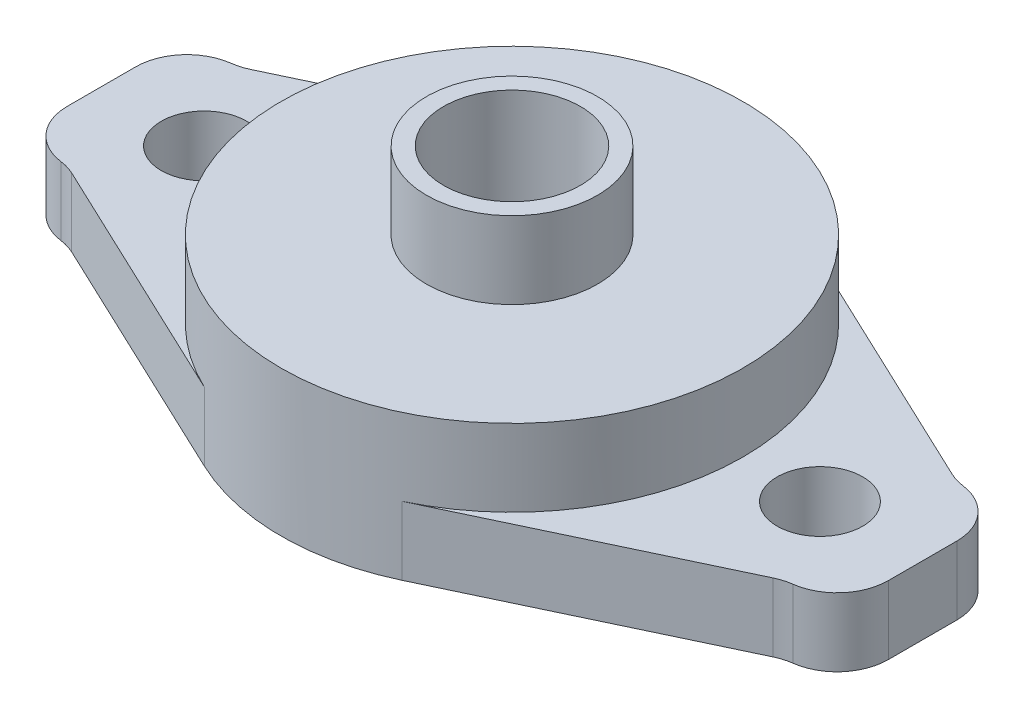
SolidWorks part; units mm, degrees
material "锌 AC41A 合金，作为铸件"
ref_plane "前视基准面" through (0, 0, 0) normal (0, 0, 1) x (1, 0, 0)
ref_plane "上视基准面" through (0, 0, 0) normal (0, 1, 0) x (1, 0, 0)
ref_plane "右视基准面" through (0, 0, 0) normal (1, 0, 0) x (0, 0, -1)
sketch "草图1" plane through (0, 0, 0) normal (0, 1, 0) x (1, 0, 0)
  line L0 (0, 0) -> (18, 0) construction
  line L1 (-20.4991, 5.237) -> (-5.773, 12.2034)
  line L2 (-21, 5) -> (21, 5)
  line L3 (-24, 2) -> (-24, -2)
  line L4 (-21, -5) -> (21, -5)
  line L5 (24, 2) -> (24, -2)
  line L6 (-24, 5) -> (24, -5) construction
  line L7 (-24, -5) -> (24, 5) construction
  line L8 (-24, 0) -> (24, 0) construction
  line L9 (0, 13.5) -> (0, -13.5) construction
  line L10 (20.4991, 5.237) -> (5.773, 12.2034)
  line L11 (20.4991, -5.237) -> (5.773, -12.2034)
  line L12 (-20.4991, -5.237) -> (-5.773, -12.2034)
  circle A0 centre (0, 0) radius 4
  circle A1 centre (0, 0) radius 13.5
  circle A2 centre (18, 0) radius 2.5
  arc A3 (-21.391, -4.9744) -> (-24, -2) centre (-21, -2) cw
  arc A4 (-21.391, 4.9744) -> (-24, 2) centre (-21, 2) ccw
  arc A5 (24, -2) -> (21.391, -4.9744) centre (21, -2) cw
  arc A6 (24, 2) -> (21.391, 4.9744) centre (21, 2) ccw
  circle A7 centre (-18, 0) radius 2.5
  arc A8 (21.391, -4.9744) -> (20.4991, -5.237) centre (21.782, -7.9488) ccw
  arc A9 (21.391, 4.9744) -> (20.4991, 5.237) centre (21.782, 7.9488) cw
  arc A10 (-21.391, -4.9744) -> (-20.4991, -5.237) centre (-21.782, -7.9488) cw
  arc A11 (-21.391, 4.9744) -> (-20.4991, 5.237) centre (-21.782, 7.9488) ccw
  dimension "D1" = 8
  dimension "D2" = 27
  dimension "D4" = 5
  dimension "D7" = 3
  dimension "D8" = 3
  dimension "D3" = 18
  dimension "D5" = 48
  dimension "D6" = 10
extrude "凸台-拉伸1" add sketch "草图1" along normal blind 4
ref_plane "基准面1" through (0, 4, 0) normal (0, 1, 0) x (1, 0, 0)
sketch "草图2" plane through (0, 4, 0) normal (0, 1, 0) x (1, 0, 0)
  circle A0 centre (0, 0) radius 4
  circle A1 centre (0, 0) radius 13.5
extrude "凸台-拉伸2" add sketch "草图2" along normal blind 4.5
ref_plane "基准面2" through (0, 8.5, 0) normal (0, 1, 0) x (1, 0, 0)
sketch "草图3" plane through (0, 8.5, 0) normal (0, 1, 0) x (1, 0, 0)
  circle A0 centre (0, 0) radius 4
  circle A1 centre (0, 0) radius 5
  dimension "D1" = 10
extrude "凸台-拉伸3" add sketch "草图3" along normal blind 4.5
